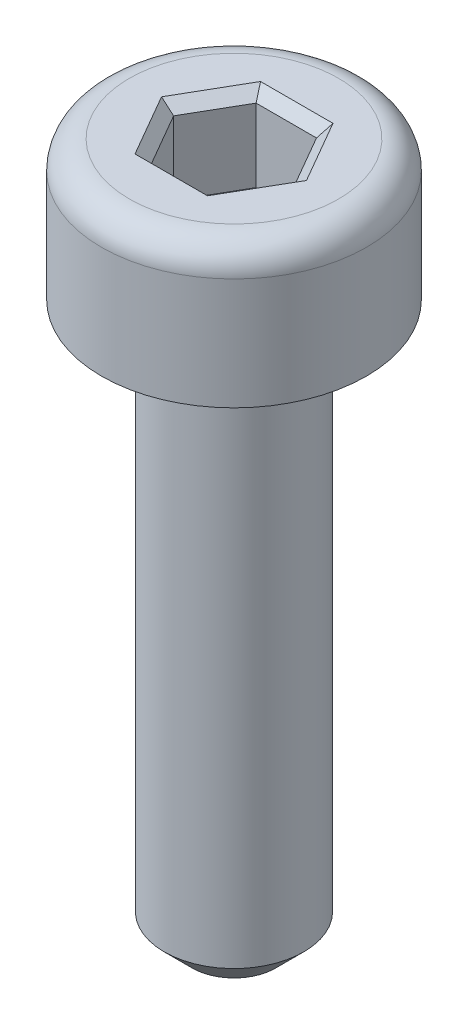
SolidWorks part; units mm, degrees
material "AISI Acier inoxydable type 316L"
ref_plane "Plan de face" through (0, 0, 0) normal (0, 0, 1) x (1, 0, 0)
ref_plane "Plan de dessus" through (0, 0, 0) normal (0, 1, 0) x (1, 0, 0)
ref_plane "Plan de droite" through (0, 0, 0) normal (1, 0, 0) x (0, 0, -1)
sketch "Esquisse1" plane through (0, 0, 0) normal (0, 0, 1) x (1, 0, 0)
  line L0 (0, 6.973) -> (0, -16.342) construction
  line L1 (1, -7.6) -> (0.6, -8)
  line L2 (0, 2) -> (1.5, 2)
  line L3 (1.9, 1.6) -> (1.9, 0)
  line L4 (1.9, 0) -> (1, 0)
  line L5 (1, 0) -> (1, -7.6)
  line L7 (0.6, -8) -> (0, -8)
  line L8 (0, -8) -> (0, 2)
  arc A0 (1.5, 2) -> (1.9, 1.6) centre (1.5, 1.6) cw
  point P9 (1, -8)
  point P13 (1.9, 2)
  dimension "D5" = 0.4
  dimension "D1" = 2
  dimension "D2" = 3.8
  dimension "D3" = 2
  dimension "D4" = 8
revolve "Révolution1" add sketch "Esquisse1" angle 360 about L0
cosmetic thread "Représentation de filetage1" parameters "D2"=1.993
sketch "Esquisse2" plane through (0, 2, 0) normal (0, 1, 0) x (1, 0, 0)
  line L0 (-0.866, 0) -> (-0.433, -0.75)
  line L1 (0.866, 0) -> (0.433, 0.75)
  line L2 (0.433, 0.75) -> (-0.433, 0.75)
  line L3 (-0.433, 0.75) -> (-0.866, 0)
  line L4 (-0.433, -0.75) -> (0.433, -0.75)
  line L5 (0.433, -0.75) -> (0.866, 0)
  circle A0 centre (0, 0) radius 0.75 construction
  dimension "D1" = 1.5
extrude "Enlèv. mat.-Extru.1" cut sketch "Esquisse2" against normal blind 1.2
chamfer "Chanfrein1" distance 0.15 angle 45 6 edges at (-0.6495, 2, -0.375) (-0.6495, 2, 0.375) (0, 2, 0.75) (0.6495, 2, 0.375) (0.6495, 2, -0.375) (0, 2, -0.75)
